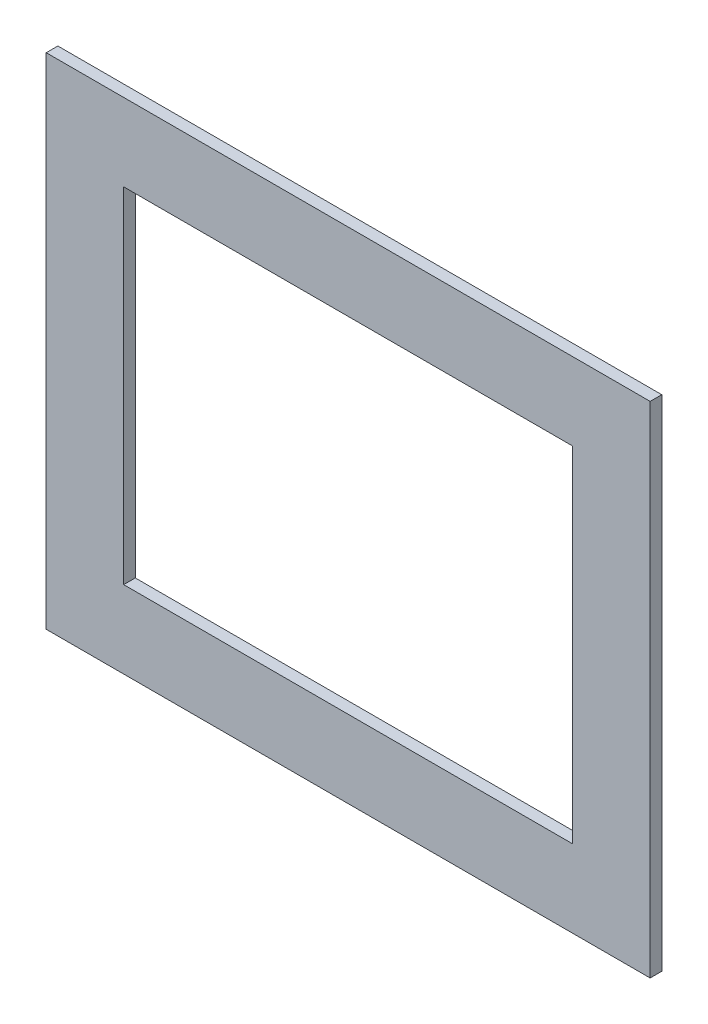
SolidWorks part; units mm, degrees
ref_plane "Front Plane" through (0, 0, 0) normal (0, 0, 1) x (1, 0, 0)
ref_plane "Top Plane" through (0, 0, 0) normal (0, 1, 0) x (1, 0, 0)
ref_plane "Right Plane" through (0, 0, 0) normal (1, 0, 0) x (0, 0, -1)
ref_plane "Plane1" through (0, 0, 2) normal (0, 0, 1) x (1, 0, 0)
sketch "Sketch2" plane through (0, 0, 2) normal (0, 0, 1) x (1, 0, 0)
  line L1 (-153, -2) -> (3, -2)
  line L2 (-153, -2) -> (-153, 127)
  line L3 (-153, 127) -> (3, 127)
  line L4 (3, -2) -> (3, 127)
  line L6 (-150, 125) -> (0, 125) construction
  line L7 (-150, 0) -> (-150, 125) construction
  line L9 (-133, 18) -> (-17, 18)
  line L10 (-133, 18) -> (-133, 107)
  line L11 (-133, 107) -> (-17, 107)
  line L12 (-17, 18) -> (-17, 107)
  dimension "D1" = 129
  dimension "D2" = 156
  dimension "D3" = 2
  dimension "D4" = 3
  dimension "D5" = 20
  dimension "D6" = 20
  dimension "D7" = 20
  dimension "D8" = 20
extrude "Boss-Extrude1" add sketch "Sketch2" along normal blind 3
